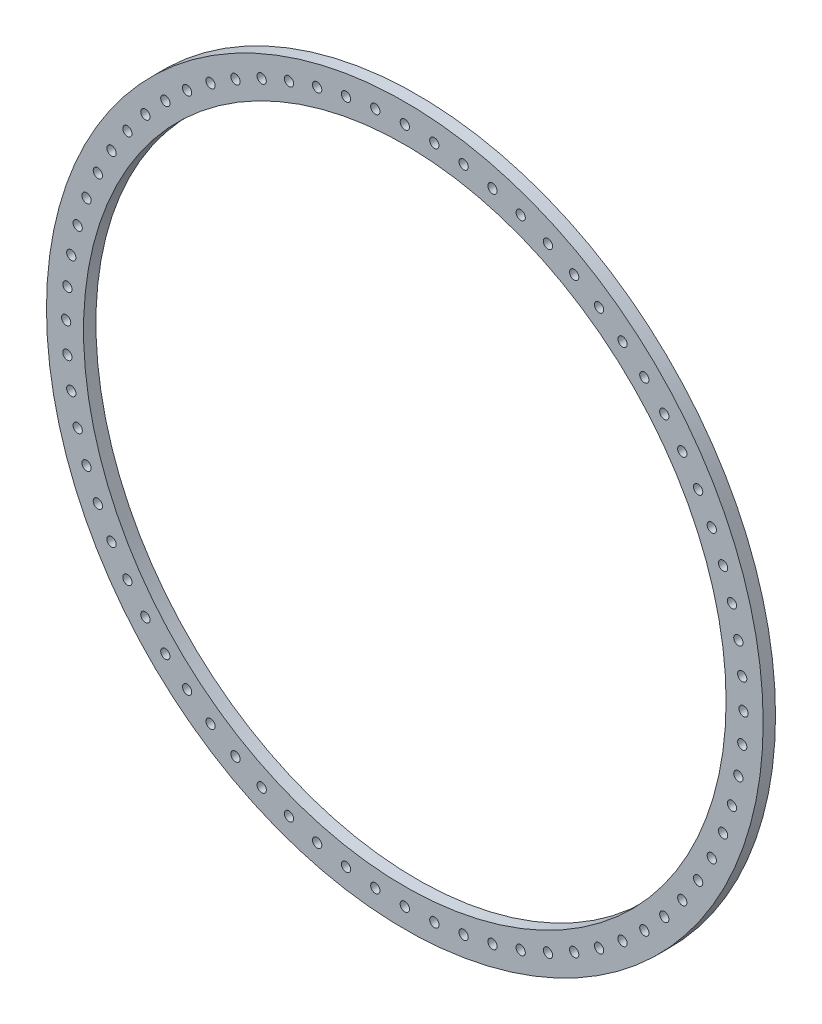
SolidWorks part; units mm, degrees
other "Markup1"
sketch "Sketch3"
ref_plane "Front Plane" through (0, 0, 0) normal (0, 0, 1) x (1, 0, 0)
ref_plane "Top Plane" through (0, 0, 0) normal (0, 1, 0) x (1, 0, 0)
ref_plane "Right Plane" through (0, 0, 0) normal (1, 0, 0) x (0, 0, -1)
sketch "Sketch2" plane through (0, 0, 0) normal (0, 0, 1) x (1, 0, 0)
  circle A0 centre (0, 0) radius 184.15
  dimension "D1" = 368.3
extrude "Boss-Extrude1" add sketch "Sketch2" along normal blind 6.35
sketch "Sketch8" plane through (0, 0, 6.35) normal (0, 0, 1) x (1, 0, 0)
  circle A0 centre (0, 0) radius 165.1
  dimension "D1" = 330.2
extrude "Cut-Extrude3" cut sketch "Sketch8" against normal through all
sketch "Sketch9" plane through (0, 0, 6.35) normal (0, 0, 1) x (1, 0, 0)
  circle A0 centre (-174.0492, 0) radius 2.3813
  dimension "D1" = 4.7625
extrude "Cut-Extrude4" cut sketch "Sketch9" against normal through all contours A0
pattern_circular "CirPattern1" count 72 over 360 about axis through (0, 0, 0) along (0, 0, 1) of "Cut-Extrude4"
